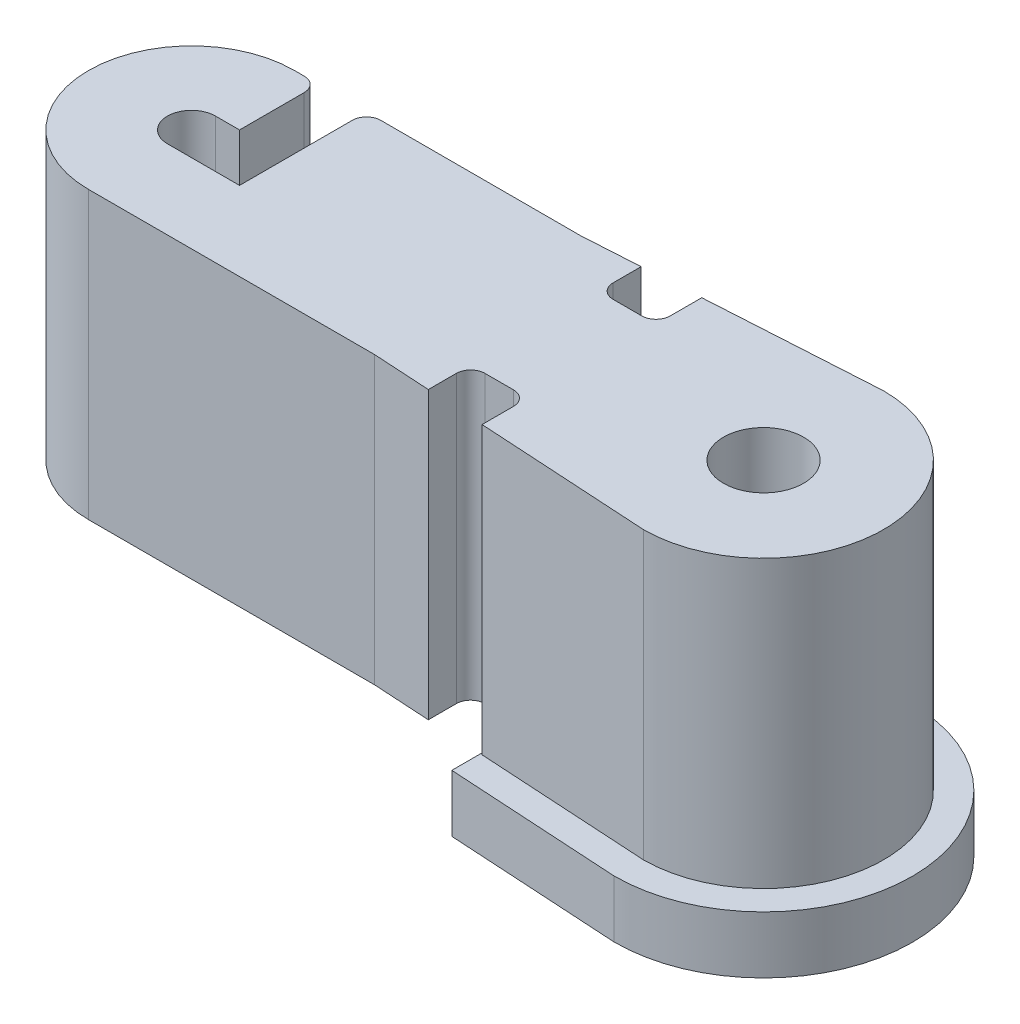
SolidWorks part; units mm, degrees
ref_plane "Front Plane" through (0, 0, 0) normal (0, 0, 1) x (1, 0, 0)
ref_plane "Top Plane" through (0, 0, 0) normal (0, 1, 0) x (1, 0, 0)
ref_plane "Right Plane" through (0, 0, 0) normal (1, 0, 0) x (0, 0, -1)
sketch "Sketch3" plane through (0, 0, 0) normal (0, 1, 0) x (1, 0, 0)
  line L0 (-5, 0.75) -> (0, 1.05) construction
  line L3 (0, -1.05) -> (-5, -0.75) construction
  line L4 (-2.5, 0.9) -> (-2, 0.93)
  line L6 (-4.25, 0) -> (-5.75, 0) construction
  line L7 (-2, 0.93) -> (-2, 0.56)
  line L8 (-2.5, 0.9) -> (-5, 0.9)
  line L9 (-2.5, 0.9) -> (-2.5, -0.9) construction
  line L10 (-2.5, -0.9) -> (-5, -0.9)
  line L11 (-5, 0.9) -> (-5, -0.9) construction
  line L12 (-2, 0.96) -> (-1.5, 0.96) construction
  line L13 (-2, 0.96) -> (-2, 0.56) construction
  line L14 (-2, 0.56) -> (-1.5, 0.56)
  line L15 (-1.5, 0.96) -> (-1.5, 0.56)
  line L16 (-1.5, -0.56) -> (-2, -0.56)
  line L17 (-1.5, -0.56) -> (-1.5, -0.96)
  line L18 (-1.5, -0.96) -> (-2, -0.96) construction
  line L19 (-2, -0.56) -> (-2, -0.96) construction
  line L21 (-2.5, -0.9) -> (-2, -0.93)
  line L22 (-2, -0.93) -> (-2, -0.56)
  line L23 (-1.5, 0.96) -> (0, 1.05)
  line L24 (0, -1.05) -> (-1.5, -0.96)
  circle A2 centre (0, 0) radius 0.6 construction
  circle A3 centre (0, 0) radius 0.4 construction
  circle A4 centre (-5, 0) radius 0.35 construction
  circle A5 centre (0, 0) radius 1.05 construction
  circle A6 centre (-5, 0) radius 0.75 construction
  arc A7 (-5, 0.9) -> (-5, -0.9) centre (-5, 0) ccw
  arc A8 (0, 1.05) -> (0, -1.05) centre (0, 0) cw
  point P4 (-2, -0.93)
  point P15 (-5, 0)
  point P16 (-2, 0.93)
  point P22 (-5, 0)
  dimension "D2" = 1.2
  dimension "D3" = 0.8
  dimension "D4" = 0.7
  dimension "D6" = 5
  dimension "D1" = 1.5
  dimension "D5" = 2.1
  dimension "D7" = 0.4
  dimension "D9" = 2.5
  dimension "D10" = 1.8
  dimension "D11" = 2.5
  dimension "D12" = 0.5
  dimension "D14" = 1.5
extrude "Boss-Extrude1" add sketch "Sketch3" along normal blind 2.5 contours L8 A7 L10 L21 L22 L16 L17 L24 A8 L23 L15 L14 L7 L4
sketch "Sketch4" plane through (0, 2.5, 0) normal (0, 1, 0) x (1, 0, 0)
  line L3 (-4.79, 0.9) -> (-4.37, 0.9)
  line L4 (-2.5, 0.9) -> (-5, 0.9) construction
  line L5 (-4.79, 0.9) -> (-4.79, 0.21)
  line L6 (-4.37, 0.9) -> (-4.37, -0.21)
  line L7 (-4.37, -0.21) -> (-5, -0.21)
  line L8 (-5, 0.21) -> (-4.79, 0.21)
  circle A0 centre (0, 0) radius 0.35
  circle A1 centre (-5, 0) radius 0.375 construction
  circle A2 centre (-5, 0) radius 0.21 construction
  arc A3 (-5, 0.21) -> (-4.9957, -0.21) centre (-5, 0) ccw
  point P9 (0, 0)
  dimension "D1" = 0.7
  dimension "D2" = 0.75
  dimension "D4" = 0.42
  dimension "D3" = 0.42
extrude "Through Holes" cut sketch "Sketch4" against normal through all
fillet "Fillet1" radius 0.125 6 edges at (-2, 1.25, 0.56) (-1.5, 1.25, 0.56) (-1.5, 1.25, -0.56) (-2, 1.25, -0.56) (-4.79, 1.25, -0.9) (-4.37, 1.25, -0.9)
sketch "Sketch5" plane through (0, 0, 0) normal (0, 1, 0) x (1, 0, 0)
  line L2 (-1.515, -1.2096) -> (-1.515, 1.2096)
  line L4 (-1.515, 1.2096) -> (-0.0079, 1.3)
  line L5 (-0.0079, -1.3) -> (-1.515, -1.2096)
  line L6 (-1.515, 1.2096) -> (-0.0079, 1.3)
  line L7 (-0.0079, -1.3) -> (-1.515, -1.2096)
  circle A1 centre (0, 0) radius 0.125
  arc A2 (-0.0079, -1.3) -> (-0.0079, 1.3) centre (0, 0) ccw
  arc A3 (-0.0079, -1.3) -> (-0.0079, 1.3) centre (0, 0) ccw
  dimension "D2" = 0.25
  dimension "D1" = 0.25
extrude "Boss-Extrude2" add sketch "Sketch5" against normal blind 0.5
